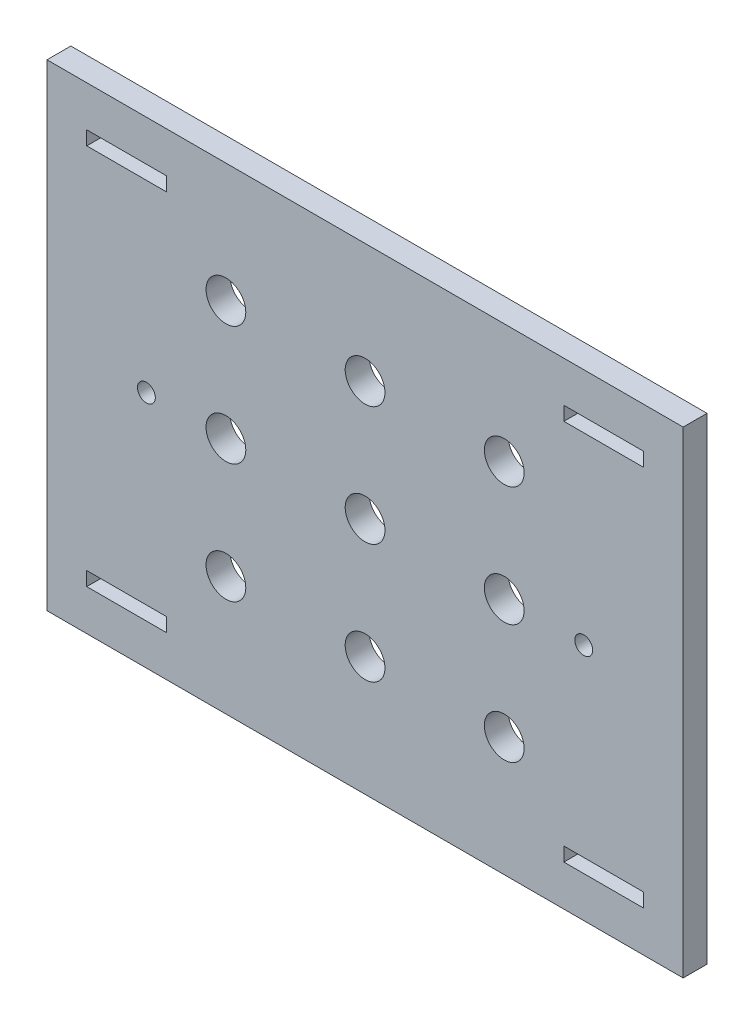
SolidWorks part; units mm, degrees
ref_plane "前视基准面" through (0, 0, 0) normal (0, 0, 1) x (1, 0, 0)
ref_plane "上视基准面" through (0, 0, 0) normal (0, 1, 0) x (1, 0, 0)
ref_plane "右视基准面" through (0, 0, 0) normal (1, 0, 0) x (0, 0, -1)
other "Configuration Table"
sketch "草图1" plane through (0, 0, 0) normal (0, 0, 1) x (1, 0, 0)
  line L1 (-80, -60) -> (80, -60)
  line L2 (-80, -60) -> (-80, 60)
  line L3 (-80, 60) -> (80, 60)
  line L4 (80, -60) -> (80, 60)
extrude "主板通用托盘160x120" add sketch "草图1" along normal blind 6
sketch "草图2" plane through (0, 0, 0) normal (0, 0, 1) x (1, 0, 0)
  line L1 (-70, -49.75) -> (-50, -49.75)
  line L2 (-70, -49.75) -> (-70, -46.25)
  line L3 (-70, -46.25) -> (-50, -46.25)
  line L4 (-50, -49.75) -> (-50, -46.25)
  line L6 (-70, 46.25) -> (-50, 46.25)
  line L7 (-70, 46.25) -> (-70, 49.75)
  line L8 (-70, 49.75) -> (-50, 49.75)
  line L9 (-50, 46.25) -> (-50, 49.75)
  line L11 (50, -49.75) -> (70, -49.75)
  line L12 (50, -49.75) -> (50, -46.25)
  line L13 (50, -46.25) -> (70, -46.25)
  line L14 (70, -49.75) -> (70, -46.25)
  line L16 (50, 46.25) -> (70, 46.25)
  line L17 (50, 46.25) -> (50, 49.75)
  line L18 (50, 49.75) -> (70, 49.75)
  line L19 (70, 46.25) -> (70, 49.75)
  circle A0 centre (-55, 0) radius 2.25
  circle A1 centre (55, 0) radius 2.25
  circle A2 centre (-35, -30) radius 5
  circle A3 centre (-35, 0) radius 5
  circle A4 centre (-35, 30) radius 5
  circle A5 centre (0, -30) radius 5
  circle A6 centre (0, 0) radius 5
  circle A7 centre (0, 30) radius 5
  circle A8 centre (35, -30) radius 5
  circle A9 centre (35, 0) radius 5
  circle A10 centre (35, 30) radius 5
extrude "安装孔散热孔与绑带槽" cut sketch "草图2" against normal through all and the other way through all
